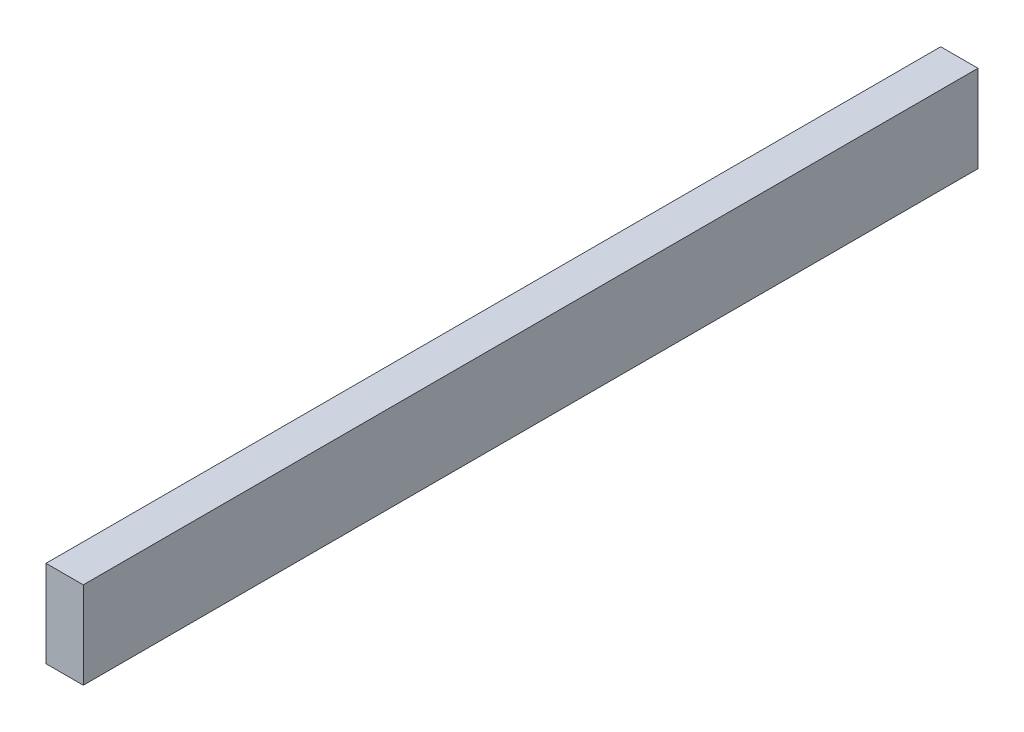
SolidWorks part; units mm, degrees
ref_plane "Front Plane" through (0, 0, 0) normal (0, 0, 1) x (1, 0, 0)
ref_plane "Top Plane" through (0, 0, 0) normal (0, 1, 0) x (1, 0, 0)
ref_plane "Right Plane" through (0, 0, 0) normal (1, 0, 0) x (0, 0, -1)
sketch "Sketch1" plane through (0, 0, 0) normal (0, 0, 1) x (1, 0, 0)
  line L0 (63.5, 1181.1) -> (63.5, 1079.5) construction
  line L1 (63.5, 1149.35) -> (25.4, 1149.35)
  line L2 (63.5, 1149.35) -> (63.5, 1060.45)
  line L3 (63.5, 1060.45) -> (25.4, 1060.45)
  line L4 (25.4, 1149.35) -> (25.4, 1060.45)
  dimension "D1" = 0
  dimension "D2" = 38.1
  dimension "D3" = 88.9
extrude "Boss-Extrude1" add sketch "Sketch1" along normal blind 914.4
